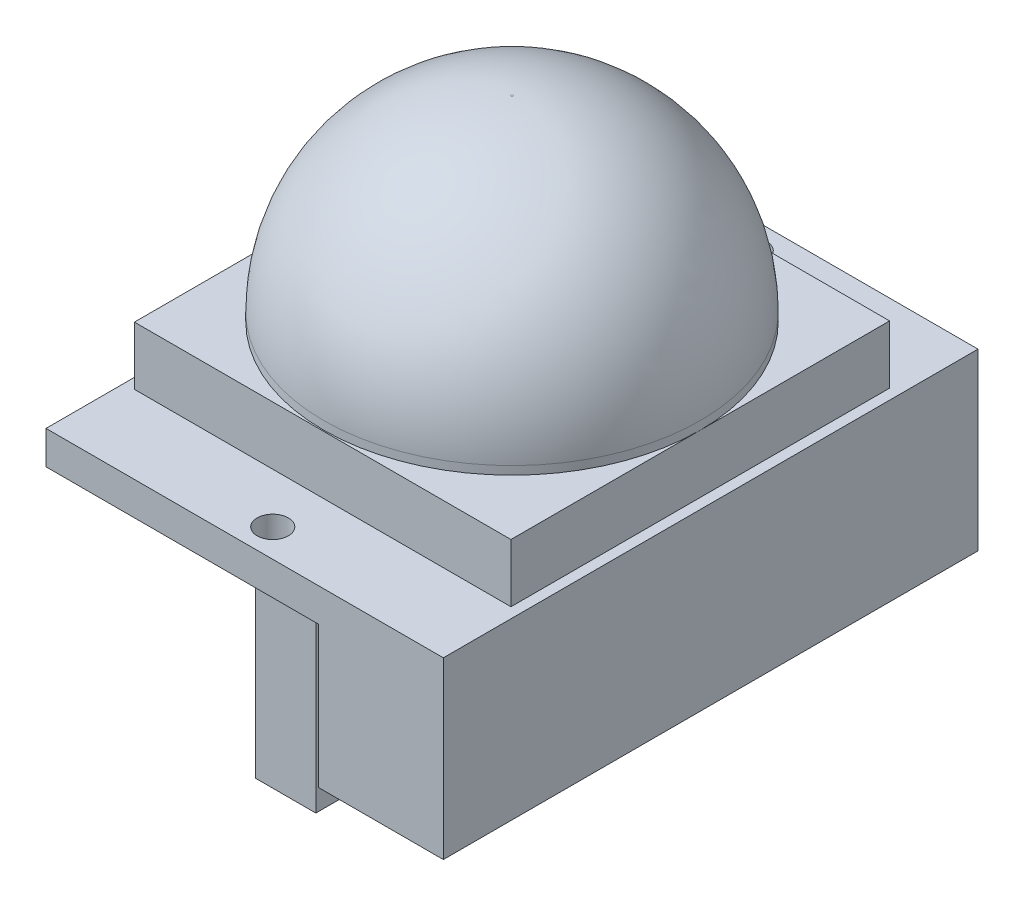
SolidWorks part; units mm, degrees
ref_plane "Front Plane" through (0, 0, 0) normal (0, 0, 1) x (1, 0, 0)
ref_plane "Top Plane" through (0, 0, 0) normal (0, 1, 0) x (1, 0, 0)
ref_plane "Right Plane" through (0, 0, 0) normal (1, 0, 0) x (0, 0, -1)
sketch "Sketch1" plane through (0, 0, 0) normal (0, 1, 0) x (1, 0, 0)
  line L1 (-12.1285, -16.3195) -> (12.1285, -16.3195)
  line L2 (-12.1285, -16.3195) -> (-12.1285, 16.3195)
  line L3 (-12.1285, 16.3195) -> (12.1285, 16.3195)
  line L4 (12.1285, -16.3195) -> (12.1285, 16.3195)
  line L5 (-12.1285, -16.3195) -> (12.1285, 16.3195) construction
  line L6 (-12.1285, 16.3195) -> (12.1285, -16.3195) construction
  point P0 (0, 0)
  dimension "D1" = 32.639
  dimension "D2" = 24.257
extrude "Boss-Extrude1" add sketch "Sketch1" along normal blind 2.032
sketch "Sketch2" plane through (0, 2.032, 0) normal (0, 1, 0) x (1, 0, 0)
  line L0 (-12.1285, -16.3195) -> (12.1285, -16.3195) construction
  line L1 (12.1285, 16.3195) -> (-12.1285, 16.3195) construction
  circle A0 centre (0, 14.605) radius 0.9525
  circle A1 centre (0, -14.605) radius 0.9525
  dimension "D1" = 1.905
  dimension "D2" = 1.905
  dimension "D4" = 1.7145
  dimension "D3" = 1.7145
extrude "Cut-Extrude1" cut sketch "Sketch2" against normal blind 2.4892
sketch "Sketch3" plane through (0, 2.032, 0) normal (0, 1, 0) x (1, 0, 0)
  line L1 (11.4935, -11.557) -> (-11.4935, -11.557)
  line L2 (11.4935, -11.557) -> (11.4935, 11.557)
  line L3 (11.4935, 11.557) -> (-11.4935, 11.557)
  line L4 (-11.4935, -11.557) -> (-11.4935, 11.557)
  line L5 (11.4935, -11.557) -> (-11.4935, 11.557) construction
  line L6 (11.4935, 11.557) -> (-11.4935, -11.557) construction
  point P0 (0, 0)
  dimension "D1" = 23.114
  dimension "D2" = 22.987
extrude "Boss-Extrude2" add sketch "Sketch3" along normal blind 3.556
sketch "Sketch4" plane through (0, 5.588, 0) normal (0, 1, 0) x (1, 0, 0)
  circle A0 centre (0, 0) radius 11.4935
extrude "Boss-Extrude3" add sketch "Sketch4" along normal blind 11.938
fillet "Fillet1" radius 11.43 1 edges at (0, 17.526, 11.4935)
sketch "Sketch5" plane through (0, 0, 0) normal (0, -1, 0) x (1, 0, 0)
  line L0 (12.1285, 16.3195) -> (12.1285, -16.3195) construction
  line L1 (12.1285, 16.3195) -> (4.5085, 16.3195)
  line L2 (12.1285, 16.3195) -> (12.1285, -16.3195)
  line L3 (12.1285, -16.3195) -> (4.5085, -16.3195)
  line L4 (4.5085, 16.3195) -> (4.5085, -16.3195)
  line L5 (-12.1285, 16.3195) -> (12.1285, 16.3195) construction
  line L6 (12.1285, -16.3195) -> (-12.1285, -16.3195) construction
  dimension "D1" = 7.62
extrude "Boss-Extrude4" add sketch "Sketch5" along normal blind 8.636
sketch "Sketch6" plane through (0, 0, 0) normal (0, -1, 0) x (1, 0, 0)
  line L0 (-12.1285, -16.3195) -> (-12.1285, 16.3195) construction
  line L1 (-12.1285, 3.5291) -> (-8.4455, 3.5291)
  line L2 (-12.1285, 3.5291) -> (-12.1285, -4.0909)
  line L3 (-12.1285, -4.0909) -> (-8.4455, -4.0909)
  line L4 (-8.4455, 3.5291) -> (-8.4455, -4.0909)
  point P6 (-12.1285, -0.2809)
  point P7 (-8.4455, -0.2809)
  dimension "D1" = 3.683
  dimension "D2" = 7.62
extrude "Boss-Extrude5" add sketch "Sketch6" along normal blind 22.86
